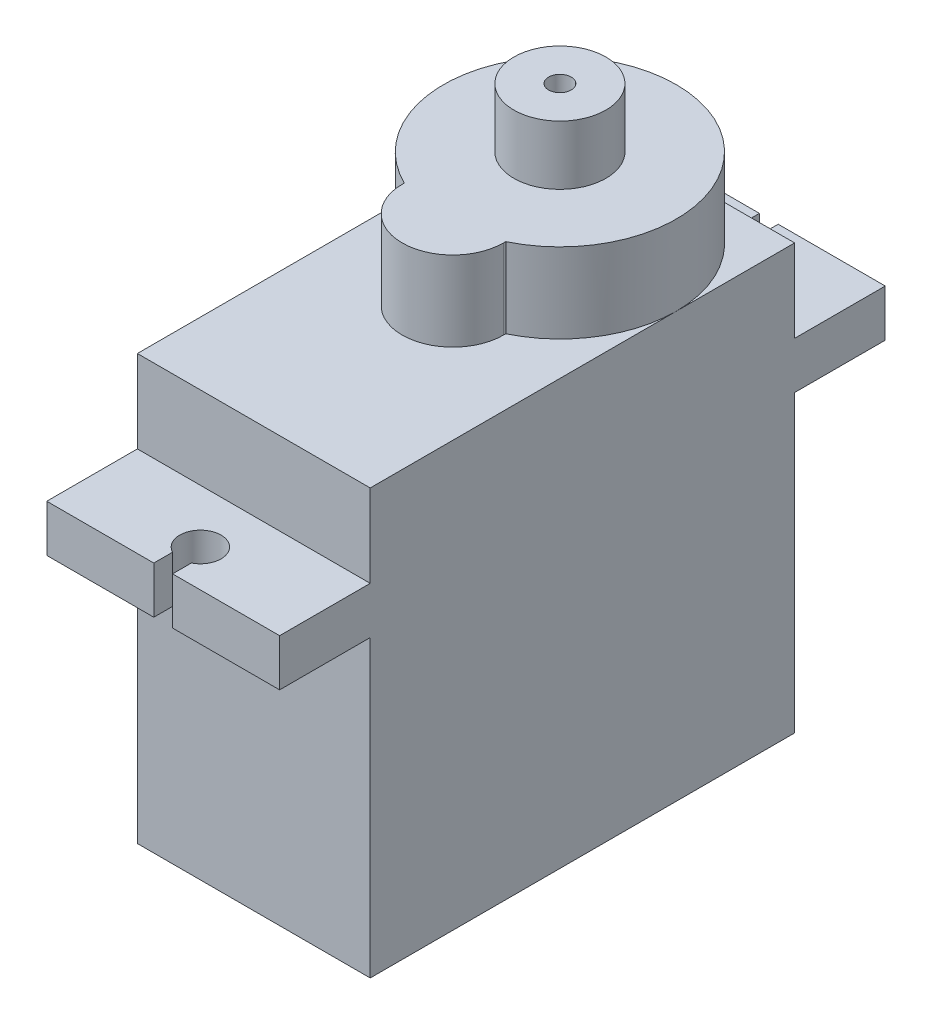
SolidWorks part; units mm, degrees
ref_plane "Ön Düzlem" through (0, 0, 0) normal (0, 0, 1) x (1, 0, 0)
ref_plane "Üst Düzlem" through (0, 0, 0) normal (0, 1, 0) x (1, 0, 0)
ref_plane "Sağ Düzlem" through (0, 0, 0) normal (1, 0, 0) x (0, 0, -1)
sketch "Çizim1" plane through (0, 0, 0) normal (0, 1, 0) x (1, 0, 0)
  line L1 (-6.2, -11.3) -> (6.2, -11.3)
  line L2 (-6.2, -11.3) -> (-6.2, 11.3)
  line L3 (-6.2, 11.3) -> (6.2, 11.3)
  line L4 (6.2, -11.3) -> (6.2, 11.3)
  line L5 (-6.2, -11.3) -> (6.2, 11.3) construction
  line L6 (-6.2, 11.3) -> (6.2, -11.3) construction
  point P0 (0, 0)
  dimension "D1" = 12.4
  dimension "D2" = 22.6
extrude "Yükseklik-Ekstrüzyon1" add sketch "Çizim1" along normal blind 22.6
ref_plane "Düzlem1" through (0, 18.2, 0) normal (0, 1, 0) x (1, 0, 0)
sketch "Çizim2" plane through (0, 18.2, 0) normal (0, 1, 0) x (1, 0, 0)
  line L0 (6.2, -11.3) -> (6.2, 11.3) construction
  line L1 (-6.2, -16.125) -> (6.2, -16.125)
  line L2 (-6.2, -16.125) -> (-6.2, 16.125)
  line L3 (-6.2, 16.125) -> (6.2, 16.125)
  line L4 (6.2, -16.125) -> (6.2, 16.125)
  line L5 (-6.2, -16.125) -> (6.2, 16.125) construction
  line L6 (-6.2, 16.125) -> (6.2, -16.125) construction
  line L7 (0, 14.1452) -> (0, 16.125) construction
  line L8 (0.5, 15.125) -> (0.5, 16.125)
  line L9 (-0.5, 15.125) -> (-0.5, 16.125)
  line L10 (-0.5, 16.125) -> (0.5, 16.125)
  line L11 (-6.2, 0) -> (6.2, 0) construction
  line L12 (0.5, -15.125) -> (0.5, -16.125)
  line L13 (-0.5, -15.125) -> (-0.5, -16.125)
  circle A0 centre (0, 14.1452) radius 1.1
  circle A1 centre (0, -14.1452) radius 1.1
  point P0 (0, 0)
  dimension "D2" = 2.2
  dimension "D1" = 32.25
  dimension "D3" = 1
  dimension "D4" = 0.5
  dimension "D5" = 28.2904
extrude "Yükseklik-Ekstrüzyon2" add sketch "Çizim2" against normal blind 2.5 contours L13 A1 L12 L1 L4 L3 L8 A0 L9 L2
ref_plane "Düzlem2" through (0, 4.8, 0) normal (0, -1, 0) x (-1, 0, 0)
sketch "Çizim3" plane through (0, 4.8, 0) normal (0, -1, 0) x (-1, 0, 0)
  line L0 (-1.8, 11.3) -> (1.8, 11.3)
  line L1 (-1.8, 11.3) -> (-1.8, 14.3)
  line L2 (1.8, 11.3) -> (1.8, 14.3)
  line L3 (-1.8, 14.3) -> (1.8, 14.3)
  line L4 (-6.2, 11.3) -> (6.2, 11.3) construction
  line L5 (-6.2, 11.3) -> (6.2, 11.3) construction
  point P8 (0, 11.3)
  dimension "D1" = 3.6
  dimension "D2" = 3
extrude "Yükseklik-Ekstrüzyon3" add sketch "Çizim3" along normal blind 1.2
sketch "Çizim4" plane through (0, 22.6, 0) normal (0, 1, 0) x (1, 0, 0)
  line L0 (-6.2, 11.3) -> (-6.2, -11.3) construction
  line L2 (6.2, -11.3) -> (6.2, 11.3) construction
  line L3 (6.2, 11.3) -> (-6.2, 11.3) construction
  line L4 (-2.7, -0.7) -> (-2.7, -0.5812)
  line L5 (2.7, -0.7) -> (2.7, -0.5812)
  circle A0 centre (0, 5) radius 6.2
  arc A1 (-2.7, -0.7) -> (2.7, -0.7) centre (0, -0.7) ccw
  point P2 (0, 11.2)
  point P8 (0, 11.3)
  point P15 (0, -3.4)
  dimension "D2" = 2.7
  dimension "D1" = 0.1
  dimension "D3" = 14.6
extrude "Yükseklik-Ekstrüzyon4" add sketch "Çizim4" along normal blind 4.25 contours A0 | L4 A1 L5 A0
sketch "Çizim5" plane through (0, 26.85, 0) normal (0, 1, 0) x (1, 0, 0)
  circle A0 centre (0, 5) radius 0.6
  arc A1 (6.2, 5) -> (-6.2, 5) centre (0, 5) ccw construction
  circle A2 centre (0, 5) radius 2.45
  arc A3 (2.7, -0.5812) -> (-2.7, -0.5812) centre (0, 5) ccw construction
  dimension "D1" = 1.2
  dimension "D2" = 4.9
ref_plane "Düzlem3" through (0, 30, 0) normal (0, 1, 0) x (1, 0, 0)
extrude "Yükseklik-Ekstrüzyon6" add sketch "Çizim5" along normal up to surface (3.15 mm away) up to plane "Düzlem3"
sketch "Çizim6" plane through (0, 0, -14.3) normal (0, 0, -1) x (-1, 0, 0)
  line L0 (-1.8, 3.6) -> (1.8, 3.6) construction
  line L1 (-0.6667, 3.6) -> (-0.5667, 3.6)
  line L2 (-0.6667, 3.6) -> (-0.6667, 4.8)
  line L3 (-0.6667, 4.8) -> (-0.5667, 4.8)
  line L4 (-0.5667, 3.6) -> (-0.5667, 4.8)
  line L5 (1.8, 4.8) -> (-1.8, 4.8) construction
  line L6 (-0.6667, 4.2) -> (-1.8, 4.2) construction
  line L7 (0.5667, 4.8) -> (0.6667, 4.8)
  line L8 (0.5667, 4.8) -> (0.5667, 3.6)
  line L9 (0.5667, 3.6) -> (0.6667, 3.6)
  line L10 (0.6667, 4.8) -> (0.6667, 3.6)
  line L11 (-1.8, 3.6) -> (-1.8, 4.8) construction
  line L12 (-0.5667, 4.2) -> (0.5667, 4.2) construction
  line L13 (0.6667, 4.2) -> (1.8, 4.2) construction
  line L14 (1.8, 3.6) -> (1.8, 4.8) construction
  dimension "D1" = 0.1
  dimension "D2" = 0.1
extrude "Kes-Ekstrüzyon1" cut sketch "Çizim6" against normal up to surface (3 mm away) up to face at (0, 7.85, -11.3)
fillet "Radyus1" radius 0.5 12 edges at (-0.6667, 4.8, -12.8) (-1.8, 4.8, -12.8) (-1.8, 3.6, -12.8) (-0.6667, 3.6, -12.8) (0.5667, 3.6, -12.8) (-0.5667, 3.6, -12.8) (-0.5667, 4.8, -12.8) (0.5667, 4.8, -12.8) (1.8, 3.6, -12.8) (0.6667, 4.8, -12.8) (0.6667, 3.6, -12.8) (1.8, 4.8, -12.8)
